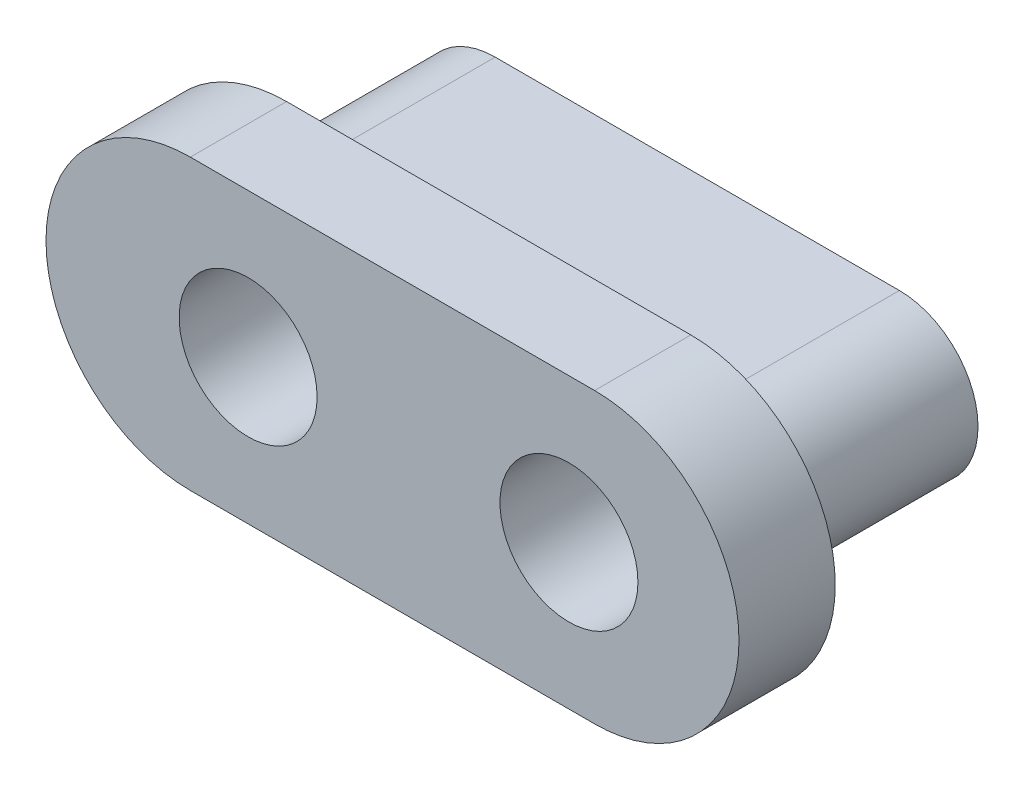
SolidWorks part; units mm, degrees
ref_plane "Front Plane" through (0, 0, 0) normal (0, 0, 1) x (1, 0, 0)
ref_plane "Top Plane" through (0, 0, 0) normal (0, 1, 0) x (1, 0, 0)
ref_plane "Right Plane" through (0, 0, 0) normal (1, 0, 0) x (0, 0, -1)
sketch "outline" plane through (0, 0, 0) normal (0, 0, 1) x (1, 0, 0)
  line L4 (-35.8988, 4.5) -> (-49.4979, 4.5)
  line L5 (-33.2202, 2) -> (-35.8988, 4.5)
  line L6 (-35.8988, -0.5) -> (-33.2202, 2)
  line L7 (-49.4979, -0.5) -> (-35.8988, -0.5)
  line L8 (-35.8988, 4.5) -> (-49.4979, 4.5)
  line L9 (-33.2202, 2) -> (-35.8988, 4.5)
  line L10 (-35.8988, -0.5) -> (-33.2202, 2)
  line L11 (-49.4979, -0.5) -> (-35.8988, -0.5)
  line L22 (-31.8152, 0) -> (-31.8152, 4)
  line L23 (-31.8152, 4) -> (-32.1105, 4)
  line L24 (-32.1105, 4) -> (-34.6206, 6.0428)
  line L25 (-35.7805, 6.5) -> (-49.4979, 6.5)
  line L26 (-49.4979, -2.5) -> (-35.7805, -2.5)
  line L27 (-34.5932, -2.071) -> (-32.1079, 0)
  line L28 (-32.1079, 0) -> (-31.8152, 0)
  line L29 (-31.8152, 0) -> (-31.8152, 4)
  line L30 (-31.8152, 4) -> (-32.1105, 4)
  line L31 (-32.1105, 4) -> (-34.6206, 6.0428)
  line L32 (-35.7805, 6.5) -> (-49.4979, 6.5)
  line L33 (-49.4979, -2.5) -> (-35.7805, -2.5)
  line L34 (-34.5932, -2.071) -> (-32.1079, 0)
  line L35 (-32.1079, 0) -> (-31.8152, 0)
  arc A1 (-49.4979, 4.5) -> (-49.4979, -0.5) centre (-49.4979, 2) ccw
  arc A2 (-49.4979, 4.5) -> (-49.4979, -0.5) centre (-49.4979, 2) ccw
  arc A5 (-34.6206, 6.0428) -> (-35.7805, 6.5) centre (-35.7805, 4.8) ccw
  arc A9 (-49.4979, 6.5) -> (-49.4979, -2.5) centre (-49.4979, 2) ccw
  arc A10 (-35.7805, -2.5) -> (-34.5932, -2.071) centre (-35.7232, -0.801) ccw
  arc A11 (-34.6206, 6.0428) -> (-35.7805, 6.5) centre (-35.7805, 4.8) ccw
  arc A12 (-49.4979, 6.5) -> (-49.4979, -2.5) centre (-49.4979, 2) ccw
  arc A13 (-35.7805, -2.5) -> (-34.5932, -2.071) centre (-35.7232, -0.801) ccw
  dimension "D1" = 0
  dimension "D2" = 0
sketch "Sketch2" plane through (0, 0, 0) normal (0, 0, 1) x (1, 0, 0)
  line L0 (-49.4979, 2) -> (-36.8979, 2) construction
  line L1 (-49.4979, 4.45) -> (-36.8979, 4.45)
  line L2 (-49.4979, -0.45) -> (-36.8979, -0.45)
  arc A0 (-49.4979, 4.45) -> (-49.4979, -0.45) centre (-49.4979, 2) ccw
  arc A1 (-36.8979, -0.45) -> (-36.8979, 4.45) centre (-36.8979, 2) ccw
  dimension "D1" = 2.45
  dimension "D2" = 12.6
extrude "Boss-Extrude1" add sketch "Sketch2" against normal blind 6.5
sketch "Sketch3" plane through (0, 0, 0) normal (0, 0, 1) x (1, 0, 0)
  line L0 (-49.4979, 6.5) -> (-36.8979, 6.5)
  line L1 (-49.4979, -2.5) -> (-36.8979, -2.5)
  arc A0 (-49.4979, 6.5) -> (-49.4979, -2.5) centre (-49.4979, 2) ccw
  arc A1 (-36.8979, -2.5) -> (-36.8979, 6.5) centre (-36.8979, 2) ccw
extrude "Boss-Extrude2" add sketch "Sketch3" along normal blind 3
sketch "Sketch4" plane through (0, 0, 3) normal (0, 0, 1) x (1, 0, 0)
  line L0 (-49.4979, 2) -> (-36.1964, 2) construction
  point P3 (-47.6979, 2)
  point P4 (-37.6979, 2)
  dimension "D1" = 10
  dimension "D2" = 1.8
hole_wizard "M4 Clearance Hole1" positions "3DSketch1" profile "Sketch5" hole size "M4" standard "BSI" end condition through all
sketch3d "3DSketch1"
  point P0 (-47.6979, 2, 3)
  point P3 (-37.6979, 2, 3)
sketch "Sketch5" plane through (-47.6979, 2, 3) normal (1, 0, 0) x (0, -1, 0)
  line L0 (0, 0) -> (0, 9.5)
  line L1 (0, 9.5) -> (2.15, 9.5)
  line L2 (2.15, 9.5) -> (2.15, 0)
  line L5 (2.15, 0) -> (0, 0)
  line L11 (0, -6.35) -> (0, 107.95) construction
  dimension "Thru Hole Dia." = 4.3
  dimension "Thru Hole Depth" = 9.5
